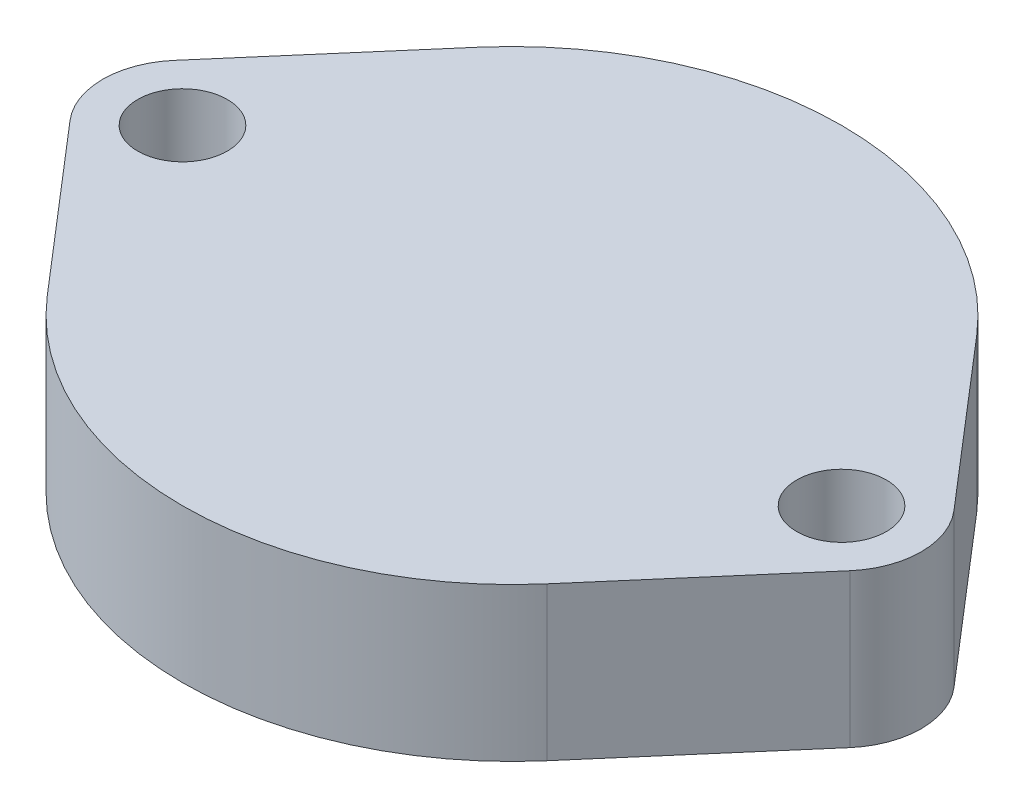
SolidWorks part; units mm, degrees
ref_plane "Front Plane" through (0, 0, 0) normal (0, 0, 1) x (1, 0, 0)
ref_plane "Top Plane" through (0, 0, 0) normal (0, 1, 0) x (1, 0, 0)
ref_plane "Right Plane" through (0, 0, 0) normal (1, 0, 0) x (0, 0, -1)
sketch "Sketch1" plane through (0, 0, 0) normal (0, 1, 0) x (1, 0, 0)
  line L0 (-15.0296, 2.0046) -> (-9.6266, 8.2836)
  line L1 (9.6266, 8.2836) -> (15.0296, 2.0046)
  line L2 (-15.0296, -2.0046) -> (-9.6266, -8.2836)
  line L3 (15.0296, -2.0046) -> (9.6266, -8.2836)
  line L5 (-55, 0) -> (55, 0) construction
  circle A0 centre (0, 0) radius 8.1661 construction
  arc A1 (-9.6266, -8.2836) -> (9.6266, -8.2836) centre (0, 0) ccw
  circle A2 centre (-12.7, 0) radius 1.7272
  circle A3 centre (12.7, 0) radius 1.7272
  arc A4 (-15.0296, 2.0046) -> (-15.0296, -2.0046) centre (-12.7, 0) ccw
  arc A5 (15.0296, -2.0046) -> (15.0296, 2.0046) centre (12.7, 0) ccw
  arc A6 (9.6266, 8.2836) -> (-9.6266, 8.2836) centre (0, 0) ccw
  point P10 (0, 0)
  point P22 (0, 0)
  point P23 (0, 0)
  dimension "D1" = 16.3322
  dimension "D2" = 25.4
  dimension "D3" = 6.1468
  dimension "D4" = 3.4544
extrude "Boss-Extrude1" add sketch "Sketch1" along normal blind 5.9055
sketch "Sketch2" plane through (0, 0, 0) normal (0, -1, 0) x (1, 0, 0)
  circle A0 centre (0, 0) radius 10.3187
  dimension "D1" = 20.6375
extrude "Boss-Extrude2" [suppressed] add sketch "Sketch2" along normal blind 28.575
sketch "Sketch3" plane through (0, 5.9055, 0) normal (0, 1, 0) x (1, 0, 0)
  circle A0 centre (0, 0) radius 8.1534
  dimension "D1" = 16.3068
extrude "Cut-Extrude1" [suppressed] cut sketch "Sketch3" against normal blind 7.62
sketch "Sketch4" plane through (0, 5.9055, 0) normal (0, 1, 0) x (1, 0, 0)
  circle A0 centre (0, 0) radius 6.7945
  dimension "D1" = 13.589
extrude "Cut-Extrude2" [suppressed] cut sketch "Sketch4" against normal blind 16.256
sketch "Sketch5" [suppressed] plane through (0, 5.9055, 0) normal (0, 1, 0) x (1, 0, 0)
  circle A0 centre (0, 0) radius 5.08
  dimension "D1" = 10.16
extrude "Cut-Extrude3" [suppressed] cut sketch "Sketch5" against normal through all
